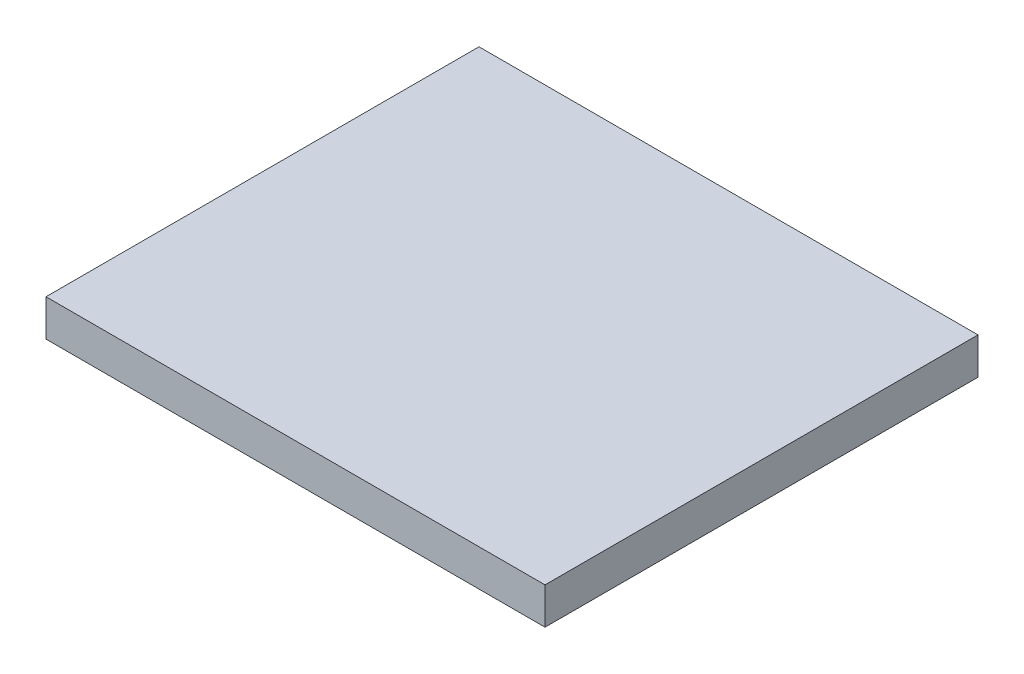
SolidWorks part; units mm, degrees
ref_plane "Front Plane" through (0, 0, 0) normal (0, 0, 1) x (1, 0, 0)
ref_plane "Top Plane" through (0, 0, 0) normal (0, 1, 0) x (1, 0, 0)
ref_plane "Right Plane" through (0, 0, 0) normal (1, 0, 0) x (0, 0, -1)
sketch "Sketch1" plane through (0, 0, 0) normal (0, 1, 0) x (1, 0, 0)
  line L1 (-34, 29.5) -> (34, 29.5)
  line L2 (-34, 29.5) -> (-34, -29.5)
  line L3 (-34, -29.5) -> (34, -29.5)
  line L4 (34, 29.5) -> (34, -29.5)
  point P4 (0, 29.5)
  point P6 (34, 0)
  dimension "D1" = 59
  dimension "D2" = 68
extrude "Boss-Extrude1" add sketch "Sketch1" along normal blind 5
